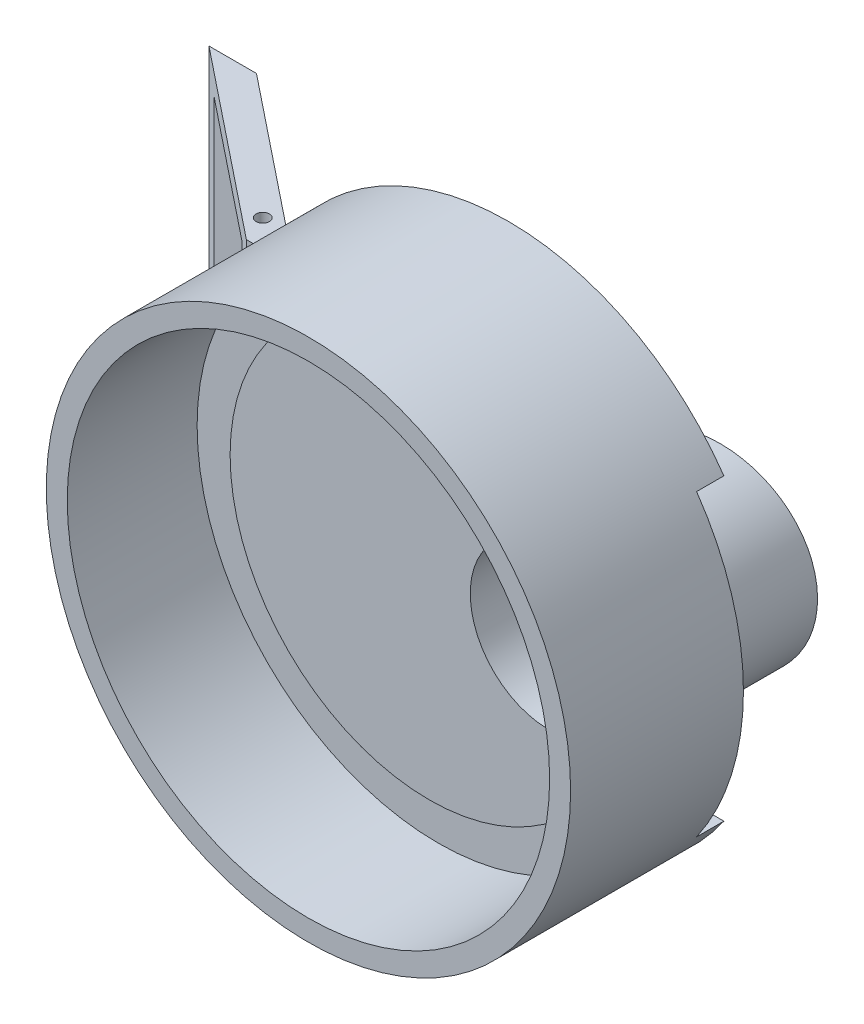
SolidWorks part; units mm, degrees
material "ABS"
ref_plane "X-Y Datum" through (0, 0, 0) normal (0, 0, 1) x (1, 0, 0)
ref_plane "X-Z Datum" through (0, 0, 0) normal (0, 1, 0) x (1, 0, 0)
ref_plane "Y-Z Datum" through (0, 0, 0) normal (1, 0, 0) x (0, 0, -1)
sketch "Sketch1" plane through (0, 0, 0) normal (0, 1, 0) x (1, 0, 0)
  line L0 (0, 0) -> (0, 100.2048) construction
  line L1 (0, 50.1024) -> (31.75, 50.1024)
  line L2 (31.75, 50.1024) -> (31.75, 25.8708)
  line L3 (31.75, 25.8708) -> (29.21, 25.8708)
  line L4 (29.21, 25.8708) -> (29.21, 40.5139)
  line L6 (0, 40.5139) -> (0, 50.1024)
  line L7 (29.21, 40.5139) -> (29.21, 41.5979)
  line L8 (29.21, 41.5979) -> (24.13, 41.5979)
  line L9 (24.13, 41.5979) -> (24.13, 40.5139)
  line L10 (24.13, 40.5139) -> (0, 40.5139)
  point P5 (24.13, 41.0559)
  dimension "D1" = 31.75
  dimension "D2" = 2.54
  dimension "D3" = 14.6431
  dimension "D4" = 15.7271
  dimension "D5" = 5.08
  dimension "D6" = 24.2316
revolve "Lid Shape" add sketch "Sketch1" angle 360 about L0
sketch "Sketch2" plane through (0, 0, -40.5139) normal (0, 0, 1) x (1, 0, 0)
  line L0 (0, 0) -> (24.13, 0) construction
  circle A0 centre (0, 0) radius 24.13 construction
  circle A2 centre (14.478, 0) radius 9.525
  circle A3 centre (0, 0) radius 24.13 construction
  dimension "D1" = 19.05
  dimension "D2" = 14.478
extrude "Lid Hole" cut sketch "Sketch2" against normal blind 50.8
sketch "Sketch5" plane through (0, 0, -50.1024) normal (0, 0, -1) x (-1, 0, 0)
  circle A0 centre (-14.478, 0) radius 12.065
  circle A1 centre (-14.478, 0) radius 9.525 construction
  dimension "D1" = 2.54
extrude "Lid Mouthpiece" add sketch "Sketch5" along normal blind 13.97
sketch "Sketch6" plane through (0, 0, -64.0724) normal (0, 0, -1) x (-1, 0, 0)
  circle A0 centre (-14.478, 0) radius 9.525
  dimension "D1" = 19.05
extrude "Lid Hole 2" cut sketch "Sketch6" against normal through all
sketch "Sketch8" plane through (0, 0, 0) normal (0, 1, 0) x (1, 0, 0)
  line L0 (-31.75, 50.1024) -> (-52.891, 66.9992)
  line L1 (31.75, 50.1024) -> (-31.75, 50.1024) construction
  line L4 (-25.9963, 50.1024) -> (-31.75, 50.1024)
  line L5 (-25.9963, 50.1024) -> (-48.5659, 68.141)
  line L6 (-48.5659, 68.141) -> (-54.3196, 68.141)
  line L7 (-52.891, 66.9992) -> (-54.3196, 68.141)
  dimension "D1" = 27.0637
  dimension "D2" = 28.8925
extrude "Lid Handle" add sketch "Sketch8" along normal mid plane 27.94
sketch "Sketch9" plane through (14.3019, 0, -17.8943) normal (0.6243, 0, -0.7812) x (-0.7812, 0, -0.6243)
  line L1 (55.0803, 10.795) -> (76.6703, 10.795)
  line L2 (55.0803, 10.795) -> (55.0803, -10.795)
  line L3 (55.0803, -10.795) -> (76.6703, -10.795)
  line L4 (76.6703, 10.795) -> (76.6703, -10.795)
  line L6 (80.4803, 13.97) -> (80.4803, -13.97) construction
  line L7 (51.5878, 13.97) -> (80.4803, 13.97) construction
  dimension "D1" = 21.59
  dimension "D2" = 21.59
  dimension "D3" = 3.81
  dimension "D4" = 3.175
sketch "Sketch10" plane through (12.0592, 0, -15.0883) normal (-0.6243, 0, 0.7812) x (0.7812, 0, 0.6243)
  line L0 (-84.9749, 13.97) -> (-84.9749, -13.97) construction
  line L1 (-81.1649, 11.43) -> (-59.5749, 11.43)
  line L2 (-81.1649, 11.43) -> (-81.1649, -10.16)
  line L3 (-81.1649, -10.16) -> (-59.5749, -10.16)
  line L4 (-59.5749, 11.43) -> (-59.5749, -10.16)
  line L5 (-84.9749, -13.97) -> (-56.0824, -13.97) construction
  dimension "D1" = 3.81
  dimension "D2" = 21.59
  dimension "D3" = 21.59
  dimension "D4" = 3.81
loft "Handle Hole" cut profiles "Sketch9", "Sketch10"
sketch "Sketch11" plane through (0, 0, -50.1024) normal (0, 0, -1) x (-1, 0, 0)
  line L0 (26.0809, 18.108) -> (-26.0809, 18.108)
  line L1 (0, 0) -> (-50.9713, 0) construction
  line L2 (26.0809, -18.108) -> (-26.0809, -18.108)
  line L5 (5.0186, 13.97) -> (28.5114, 13.97)
  line L7 (5.0186, -13.97) -> (28.5114, -13.97)
  line L9 (5.0186, 13.97) -> (5.0186, -13.97)
  arc A0 (-26.0809, 18.108) -> (-26.0809, -18.108) centre (0, 0) ccw
  arc A2 (28.5114, 13.97) -> (28.5114, -13.97) centre (0, 0) ccw
extrude "Slot for Cover" cut sketch "Sketch11" against normal blind 3.302
sketch "Sketch12" plane through (0, 0, 0) normal (0, 1, 0) x (1, 0, 0)
  line L0 (2.3574, 57.3507) -> (26.6285, 60.9956)
  line L3 (26.6285, 60.9956) -> (26.6285, 46.7716) construction
  line L4 (2.3574, 46.7716) -> (2.3574, 57.3507) construction
  line L6 (2.3574, 57.3507) -> (2.3574, 67.1403)
  line L7 (2.3574, 67.1403) -> (26.6285, 67.1403)
  line L8 (26.6285, 67.1403) -> (26.6285, 60.9956)
  line L9 (26.6285, 60.9956) -> (2.3574, 57.3507)
  line L10 (2.3574, 67.1403) -> (2.3574, 57.3507)
  line L11 (26.6285, 67.1403) -> (26.6285, 60.9956)
  dimension "D1" = 14.224
  dimension "D2" = 10.5791
extrude "Angled Mouthpiece Cut" cut sketch "Sketch12" against normal mid plane 25.4 contours L8 L7 L6 L0
sketch "Sketch15" plane through (0, 13.97, 0) normal (0, 1, 0) x (1, 0, 0)
  circle A0 centre (-33.0501, 53.3872) radius 0.811
extrude "Cut-Extrude3" cut sketch "Sketch15" against normal up to surface (27.94 mm away)
